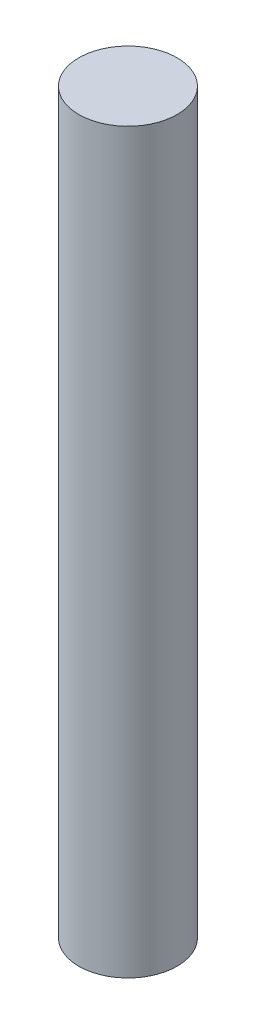
SolidWorks part; units mm, degrees
material "Copper"
ref_plane "Front Plane" through (0, 0, 0) normal (0, 0, 1) x (1, 0, 0)
ref_plane "Top Plane" through (0, 0, 0) normal (0, 1, 0) x (1, 0, 0)
ref_plane "Right Plane" through (0, 0, 0) normal (1, 0, 0) x (0, 0, -1)
sketch "Sketch1" plane through (0, 0, 0) normal (0, 1, 0) x (1, 0, 0)
  circle A0 centre (0, 0) radius 2
sketch "Sketch2" plane through (0, 0, 0) normal (0, 1, 0) x (1, 0, 0)
  circle A0 centre (0, 0) radius 2
extrude "Boss-Extrude1" add sketch "Sketch2" along normal blind 30
